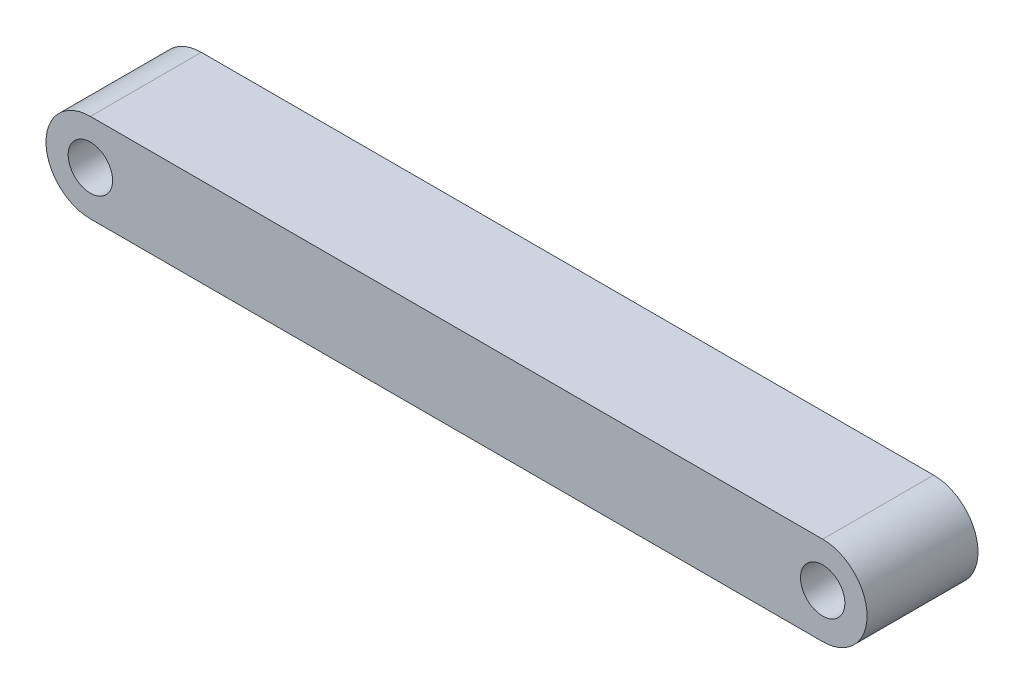
SolidWorks part; units mm, degrees
ref_plane "Alzado" through (0, 0, 0) normal (0, 0, 1) x (1, 0, 0)
ref_plane "Planta" through (0, 0, 0) normal (0, 1, 0) x (1, 0, 0)
ref_plane "Vista lateral" through (0, 0, 0) normal (1, 0, 0) x (0, 0, -1)
sketch "Croquis1" plane through (0, 0, 0) normal (0, 0, 1) x (1, 0, 0)
  line L0 (0, 4) -> (66, 4)
  line L1 (0, 0) -> (66, 0) construction
  line L2 (0, -4) -> (66, -4)
  arc A0 (0, 4) -> (0, -4) centre (0, 0) ccw
  circle A1 centre (0, 0) radius 2
  arc A2 (66, -4) -> (66, 4) centre (66, 0) ccw
  circle A3 centre (66, 0) radius 2
  dimension "D1" = 8
  dimension "D2" = 4
  dimension "D3" = 4
  dimension "D4" = 66
extrude "Saliente-Extruir1" add sketch "Croquis1" along normal blind 10
